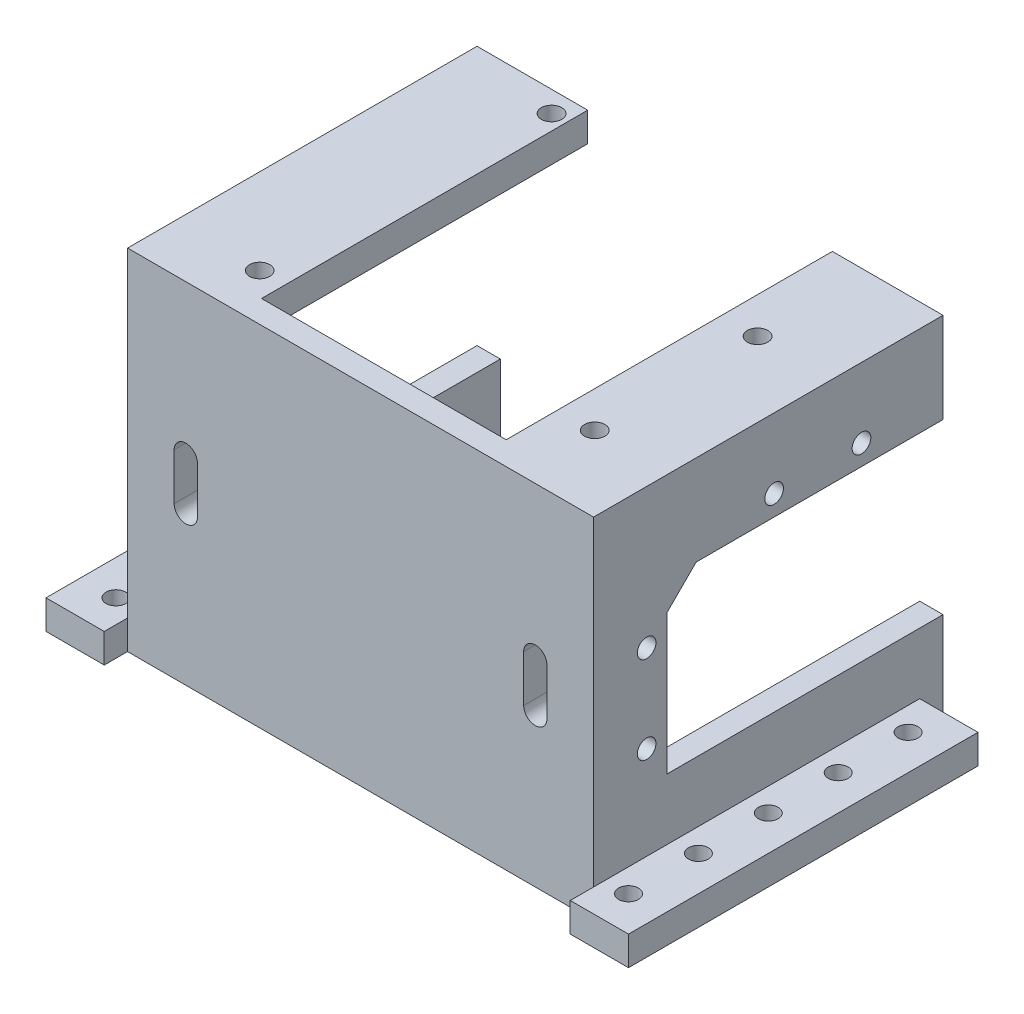
SolidWorks part; units mm, degrees
ref_plane "前视基准面" through (0, 0, 0) normal (0, 0, 1) x (1, 0, 0)
ref_plane "上视基准面" through (0, 0, 0) normal (0, 1, 0) x (1, 0, 0)
ref_plane "右视基准面" through (0, 0, 0) normal (1, 0, 0) x (0, 0, -1)
sketch "草图1" plane through (0, 0, 0) normal (0, 1, 0) x (1, 0, 0)
  line L1 (-40, -30) -> (40, -30)
  line L2 (-40, -30) -> (-40, 30)
  line L3 (-40, 30) -> (40, 30)
  line L4 (40, -30) -> (40, 30)
  line L5 (-40, -30) -> (40, 30) construction
  line L6 (-40, 30) -> (40, -30) construction
  point P0 (0, 0)
  dimension "D1" = 80
  dimension "D2" = 60
extrude "凸台-拉伸1" add sketch "草图1" along normal mid plane 60
sketch "草图2" plane through (0, 30, 0) normal (0, 1, 0) x (1, 0, 0)
  line L0 (40, 30) -> (-40, 30) construction
  line L1 (-36, -26) -> (36, -26)
  line L2 (-36, -26) -> (-36, 30)
  line L3 (-36, 30) -> (36, 30)
  line L4 (36, -26) -> (36, 30)
  line L5 (-36, -26) -> (36, 30) construction
  line L6 (-36, 30) -> (36, -26) construction
  line L7 (-40, 30) -> (-40, -30) construction
  line L8 (-40, -30) -> (40, -30) construction
  point P0 (0, 2)
  dimension "D1" = 4
  dimension "D2" = 4
extrude "切除-拉伸1" cut sketch "草图2" against normal blind 70
sketch "草图3" plane through (40, 0, 0) normal (1, 0, 0) x (0, 0, -1)
  line L0 (30, 30) -> (30, -30) construction
  line L1 (-17.3857, 14.5) -> (30, 14.5)
  line L2 (-17.3857, 14.5) -> (-17.3857, -14.5)
  line L3 (-17.3857, -14.5) -> (30, -14.5)
  line L4 (30, 14.5) -> (30, -14.5)
  line L5 (-17.3857, 14.5) -> (30, -14.5) construction
  line L6 (-17.3857, -14.5) -> (30, 14.5) construction
  point P0 (6.3072, 0)
  dimension "D1" = 29
extrude "切除-拉伸2" cut sketch "草图3" against normal blind 80
sketch "草图4" plane through (0, -30, 0) normal (0, -1, 0) x (1, 0, 0)
  line L0 (-40, -30) -> (-40, 30) construction
  line L5 (-40, 34) -> (-50, 34)
  line L6 (-40, 34) -> (-40, -26)
  line L7 (-40, -26) -> (-50, -26)
  line L8 (-50, 34) -> (-50, -26)
  line L9 (0, -55) -> (0, 55) construction
  line L10 (50, 34) -> (50, -26)
  line L11 (40, -26) -> (50, -26)
  line L12 (40, 34) -> (40, -26)
  line L13 (40, 34) -> (50, 34)
  line L14 (-40, 30) -> (40, 30) construction
  dimension "D1" = 100
  dimension "D2" = 60
  dimension "D3" = 4
extrude "凸台-拉伸2" add sketch "草图4" against normal blind 5
sketch "草图5" plane through (0, -25, 0) normal (0, 1, 0) x (1, 0, 0)
  line L0 (-50, -34) -> (-50, 26) construction
  line L1 (-50, 26) -> (-40, 26) construction
  line L2 (0, -55) -> (0, 55) construction
  circle A0 centre (-44, 20) radius 1.7
  circle A1 centre (-44, 8) radius 1.7
  circle A2 centre (-44, -4) radius 1.7
  circle A3 centre (-44, -16) radius 1.7
  circle A4 centre (-44, -28) radius 1.7
  circle A5 centre (44, -28) radius 1.7
  circle A6 centre (44, -16) radius 1.7
  circle A7 centre (44, -4) radius 1.7
  circle A8 centre (44, 8) radius 1.7
  circle A9 centre (44, 20) radius 1.7
  dimension "D1" = 3.4
  dimension "D2" = 6
  dimension "D3" = 6
  dimension "D4" = 5
extrude "切除-拉伸3" cut sketch "草图5" against normal blind 25
sketch "草图6" plane through (0, 30, 0) normal (0, 1, 0) x (1, 0, 0)
  line L0 (-36, -26) -> (36, -26) construction
  line L1 (-36, 30) -> (-21, 30)
  line L2 (-36, 30) -> (-36, -26)
  line L3 (-36, -26) -> (-21, -26)
  line L4 (-21, 30) -> (-21, -26)
  line L5 (0, -55) -> (0, 55) construction
  line L6 (21, 30) -> (21, -26)
  line L7 (36, -26) -> (21, -26)
  line L8 (36, 30) -> (36, -26)
  line L9 (36, 30) -> (21, 30)
  dimension "D1" = 15
extrude "凸台-拉伸3" add sketch "草图6" against normal blind 5
sketch "草图8" plane through (0, 30, 0) normal (0, 1, 0) x (1, 0, 0)
  circle A0 centre (-25.32, -22) radius 1.75
  circle A1 centre (-23.61, 26.395) radius 1.75
  circle A2 centre (27.2, 10.96) radius 1.75
  circle A3 centre (27.2, -17) radius 1.75
  dimension "D1" = 3.5
  dimension "D2" = 3.5
  dimension "D3" = 3.5
  dimension "D4" = 3.5
extrude "切除-拉伸5" cut sketch "草图8" against normal blind 10
chamfer "倒角1" distance 5 angle 45 2 edges at (38, 14.5, 17.3857) (-38, 14.5, 17.3857)
sketch "草图10" plane through (0, 0, 30) normal (0, 0, 1) x (1, 0, 0)
  line L2 (-30, 4) -> (-30, -4) construction
  line L3 (-28, 4) -> (-28, -4)
  line L4 (-32, 4) -> (-32, -4)
  line L5 (0, -33) -> (0, 33) construction
  line L6 (30, 4) -> (30, -4) construction
  line L7 (28, 4) -> (28, -4)
  line L8 (32, 4) -> (32, -4)
  arc A2 (-28, 4) -> (-32, 4) centre (-30, 4) ccw
  arc A3 (-32, -4) -> (-28, -4) centre (-30, -4) ccw
  arc A4 (28, 4) -> (32, 4) centre (30, 4) cw
  arc A5 (32, -4) -> (28, -4) centre (30, -4) cw
  point P2 (-30, 0)
  point P12 (30, 0)
  dimension "D1" = 8
  dimension "D2" = 30
  dimension "D3" = 2
extrude "切除-拉伸8" cut sketch "草图10" against normal blind 10
sketch "草图11" plane through (-40, 0, 0) normal (-1, 0, 0) x (0, 0, 1)
  line L0 (-30, 14.5) -> (12.3857, 14.5) construction
  line L1 (-30, 30) -> (-30, 14.5) construction
  circle A0 centre (-16, 18) radius 1.6
  circle A1 centre (-1, 18) radius 1.6
  point P7 (0, 0)
  dimension "D1" = 3.2
  dimension "D2" = 3.2
  dimension "D3" = 15
  dimension "D4" = 3.5
  dimension "D5" = 14
extrude "切除-拉伸9" cut sketch "草图11" against normal blind 100
sketch "草图12" plane through (-40, 0, 0) normal (-1, 0, 0) x (0, 0, 1)
  line L0 (17.3857, 9.5) -> (17.3857, -14.5) construction
  circle A0 centre (20.8857, 6) radius 1.6
  circle A1 centre (20.8857, -9) radius 1.6
  dimension "D1" = 3.2
  dimension "D2" = 3.2
  dimension "D3" = 15
  dimension "D4" = 3.5
  dimension "D5" = 6
extrude "切除-拉伸10" cut sketch "草图12" against normal blind 120
